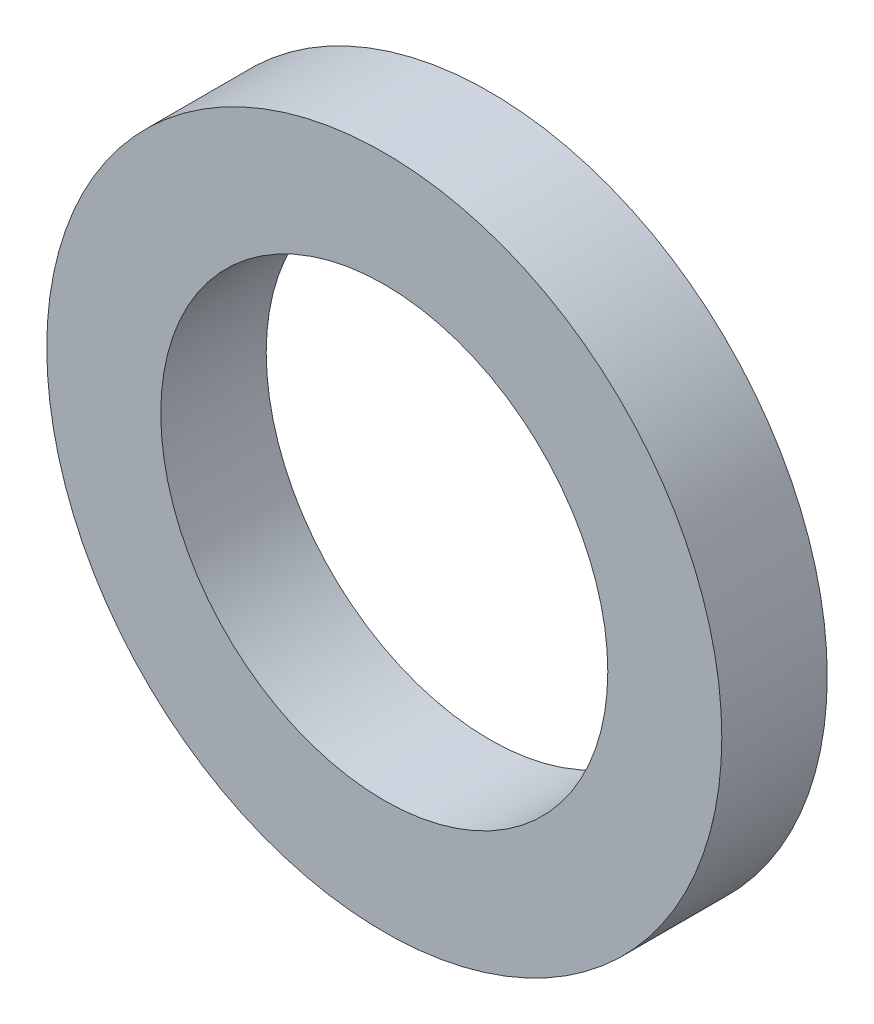
SolidWorks part; units mm, degrees
ref_plane "Front Plane" through (0, 0, 0) normal (0, 0, 1) x (1, 0, 0)
ref_plane "Top Plane" through (0, 0, 0) normal (0, 1, 0) x (1, 0, 0)
ref_plane "Right Plane" through (0, 0, 0) normal (1, 0, 0) x (0, 0, -1)
sketch "Sketch1" plane through (0, 0, 0) normal (0, 0, 1) x (1, 0, 0)
  circle A0 centre (0, 0) radius 3.18
  circle A1 centre (0, 0) radius 4.802
  dimension "D1" = 6.36
extrude "Boss-Extrude1" add sketch "Sketch1" along normal blind 1.5
